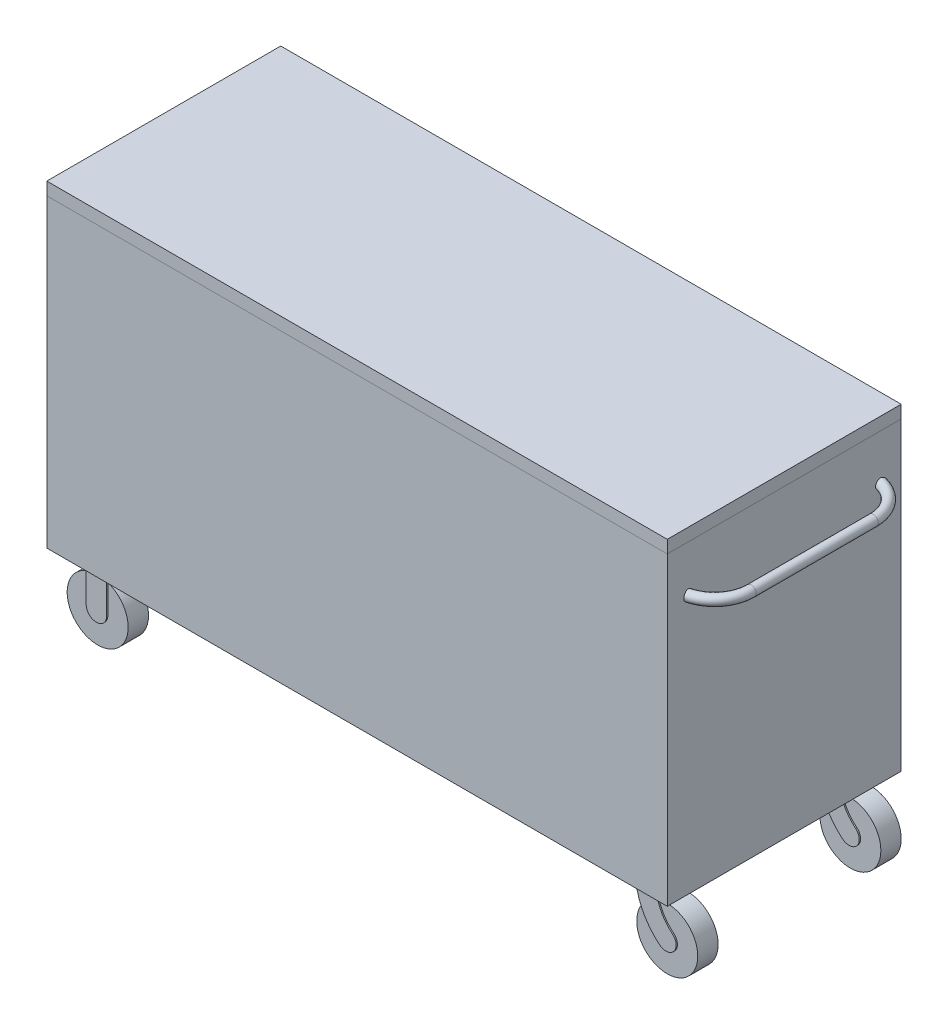
SolidWorks part; units mm, degrees
material "Plain Carbon Steel"
ref_plane "Front Plane" through (0, 0, 0) normal (0, 0, 1) x (1, 0, 0)
ref_plane "Top Plane" through (0, 0, 0) normal (0, 1, 0) x (1, 0, 0)
ref_plane "Right Plane" through (0, 0, 0) normal (1, 0, 0) x (0, 0, -1)
sketch "Sketch1" plane through (0, 0, 0) normal (0, 1, 0) x (1, 0, 0)
  line L1 (-774.7, -292.1) -> (774.7, -292.1)
  line L2 (-774.7, -292.1) -> (-774.7, 292.1)
  line L3 (-774.7, 292.1) -> (774.7, 292.1)
  line L4 (774.7, -292.1) -> (774.7, 292.1)
  line L5 (-774.7, -292.1) -> (774.7, 292.1) construction
  line L6 (-774.7, 292.1) -> (774.7, -292.1) construction
  point P0 (0, 0)
  dimension "D1" = 1549.4
  dimension "D2" = 584.2
extrude "Boss-Extrude1" add sketch "Sketch1" against normal blind 31.75
sketch "Sketch2" plane through (0, -31.75, 0) normal (0, -1, 0) x (1, 0, 0)
  line L4 (774.7, -292.1) -> (774.7, 292.1)
  line L5 (774.7, 292.1) -> (-774.7, 292.1)
  line L6 (-774.7, 292.1) -> (-774.7, -292.1)
  line L7 (-774.7, -292.1) -> (774.7, -292.1)
  line L8 (774.7, -292.1) -> (774.7, 292.1)
  line L9 (774.7, 292.1) -> (-774.7, 292.1)
  line L10 (-774.7, 292.1) -> (-774.7, -292.1)
  line L11 (-774.7, -292.1) -> (774.7, -292.1)
  dimension "D1" = 0
extrude "Boss-Extrude2" add sketch "Sketch2" along normal blind 762 separate body
ref_plane "Plane1" through (0, -146.05, 0) normal (0, 1, 0) x (1, 0, 0)
sketch "Sketch3" plane through (0, -146.05, 0) normal (0, 1, 0) x (1, 0, 0)
  line L0 (844.55, 152.4) -> (844.55, -152.4)
  line L1 (774.7, -292.1) -> (774.7, 292.1) construction
  line L2 (774.7, 292.1) -> (774.7, -292.1) construction
  arc A0 (844.55, -152.4) -> (774.7, -241.3) centre (753.0523, -152.4) cw
  arc A1 (844.55, 152.4) -> (774.7, 241.3) centre (753.0523, 152.4) ccw
  point P10 (844.55, 0)
  dimension "D1" = 69.85
  dimension "D2" = 482.6
  dimension "D3" = 304.8
sweep "Sweep1" add path "Sketch3" circular profile diameter 25.4 parameters "D3"=25.4
ref_plane "Plane2" through (0, 0, 228.6) normal (0, 0, 1) x (1, 0, 0)
sketch "Sketch13" plane through (0, 0, 228.6) normal (0, 0, 1) x (1, 0, 0)
  line L0 (774.7, -793.75) -> (774.7, -31.75) construction
  line L1 (-774.7, -793.75) -> (-774.7, -31.75) construction
  line L2 (-774.7, 0) -> (774.7, 0) construction
  circle A0 centre (736.6, -901.7) radius 76.2
  circle A1 centre (-685.8, -901.7) radius 76.2
  point P8 (736.6, -977.9)
  dimension "D3" = 152.4
  dimension "D1" = 38.1
  dimension "D2" = 88.9
  dimension "D4" = 977.9
extrude "Boss-Extrude3" add sketch "Sketch13" along normal mid plane 50.8 separate body
sketch "Sketch14" plane through (0, 0, 254) normal (0, 0, 1) x (1, 0, 0)
  line L0 (-711.2, -793.75) -> (-660.4, -793.75)
  line L1 (774.7, -793.75) -> (-774.7, -793.75) construction
  line L2 (-660.4, -793.75) -> (-660.4, -901.7)
  line L3 (-711.2, -901.7) -> (-711.2, -793.75)
  line L4 (660.4, -793.75) -> (711.2, -793.75)
  line L5 (-660.4, -793.75) -> (660.4, -793.75) construction
  arc A0 (-660.4, -901.7) -> (-711.2, -901.7) centre (-685.8, -901.7) cw
  arc A1 (711.2, -793.75) -> (752.7898, -882.1283) centre (825.8969, -793.75) ccw
  arc A2 (752.7898, -882.1283) -> (720.4102, -921.2717) centre (736.6, -901.7) cw
  arc A3 (720.4102, -921.2717) -> (660.4, -793.75) centre (825.8969, -793.75) cw
  circle A4 centre (736.6, -901.7) radius 76.2 construction
  circle A5 centre (-685.8, -901.7) radius 76.2 construction
  point P18 (0, -793.75)
  dimension "D1" = 50.8
extrude "Boss-Extrude4" add sketch "Sketch14" along normal mid plane 6.35
mirror "Mirror1" about plane through (0, 0, 228.6) normal (0, 0, 1) of "Boss-Extrude4"
mirror "Mirror2" about plane through (0, 0, 0) normal (0, 0, 1) of bodies 108 109
